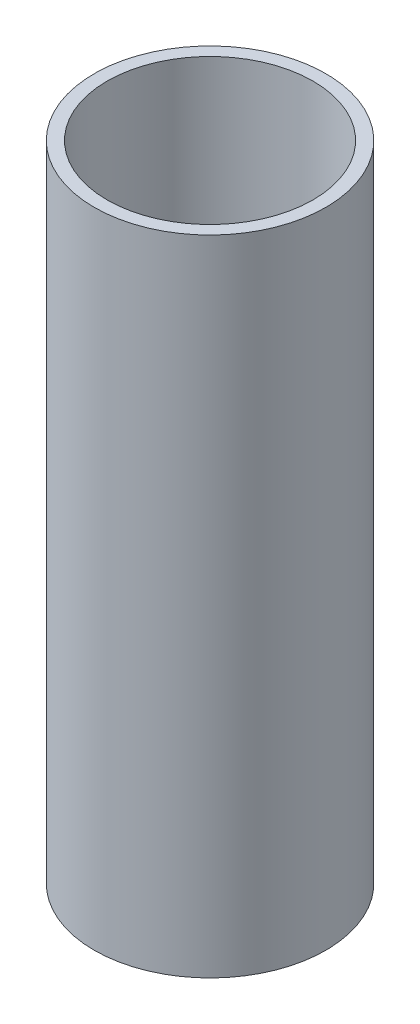
SolidWorks part; units mm, degrees
material "AISI 304"
ref_plane "Front Plane" through (0, 0, 0) normal (0, 0, 1) x (1, 0, 0)
ref_plane "Top Plane" through (0, 0, 0) normal (0, 1, 0) x (1, 0, 0)
ref_plane "Right Plane" through (0, 0, 0) normal (1, 0, 0) x (0, 0, -1)
sketch "Sketch1" plane through (0, 0, 0) normal (0, 1, 0) x (1, 0, 0)
  circle A0 centre (0, 0) radius 45
  circle A1 centre (0, 0) radius 40
  dimension "D1" = 90
  dimension "D2" = 80
extrude "Boss-Extrude1" add sketch "Sketch1" along normal blind 250 contours A1 | A0
